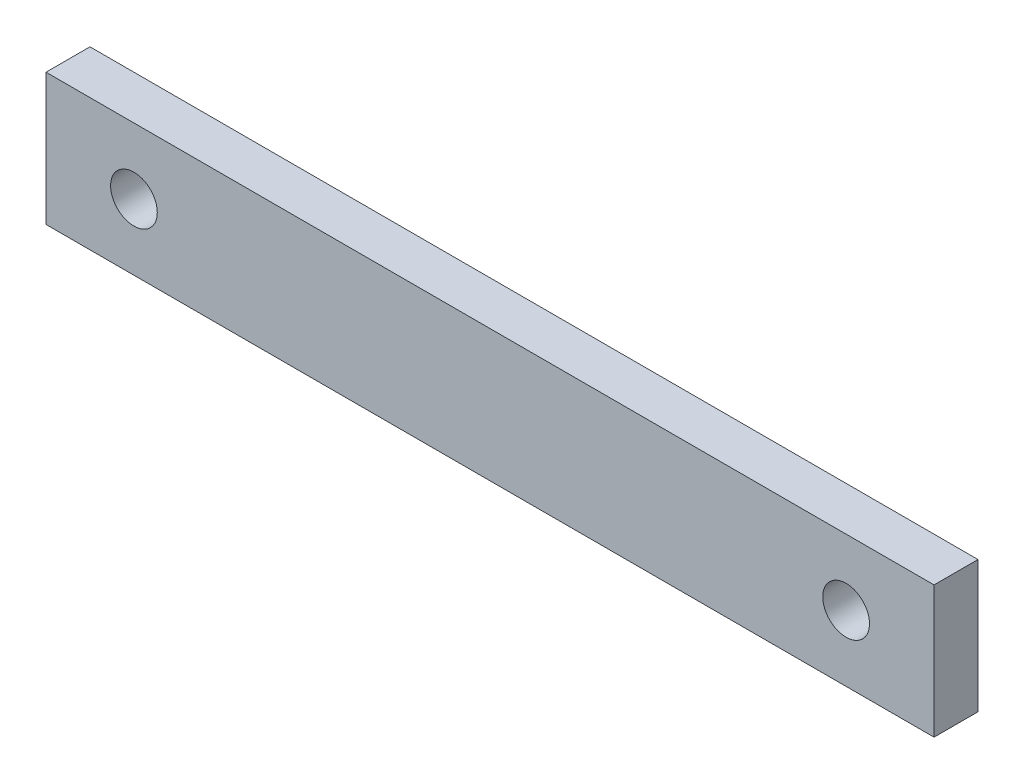
SolidWorks part; units mm, degrees
ref_plane "Front Plane" through (0, 0, 0) normal (0, 0, 1) x (1, 0, 0)
ref_plane "Top Plane" through (0, 0, 0) normal (0, 1, 0) x (1, 0, 0)
ref_plane "Right Plane" through (0, 0, 0) normal (1, 0, 0) x (0, 0, -1)
sketch "Sketch1" plane through (0, 0, 0) normal (0, 0, 1) x (1, 0, 0)
  line L1 (-64.135, -9.525) -> (64.135, -9.525)
  line L2 (-64.135, -9.525) -> (-64.135, 9.525)
  line L3 (-64.135, 9.525) -> (64.135, 9.525)
  line L4 (64.135, -9.525) -> (64.135, 9.525)
  line L5 (-64.135, -9.525) -> (64.135, 9.525) construction
  line L6 (-64.135, 9.525) -> (64.135, -9.525) construction
  point P0 (0, 0)
  dimension "D1" = 19.05
  dimension "D2" = 128.27
extrude "Boss-Extrude1" add sketch "Sketch1" along normal blind 6.35
sketch "Sketch2" plane through (0, 0, 6.35) normal (0, 0, 1) x (1, 0, 0)
  line L0 (-64.135, 9.525) -> (-64.135, -9.525) construction
  line L1 (64.135, -9.525) -> (64.135, 9.525) construction
  circle A0 centre (-51.435, 0) radius 3.3734
  circle A1 centre (51.435, 0) radius 3.3734
  dimension "D1" = 6.7469
  dimension "D2" = 6.7469
  dimension "D3" = 12.7
  dimension "D4" = 12.7
extrude "Cut-Extrude1" cut sketch "Sketch2" against normal blind 6.35
